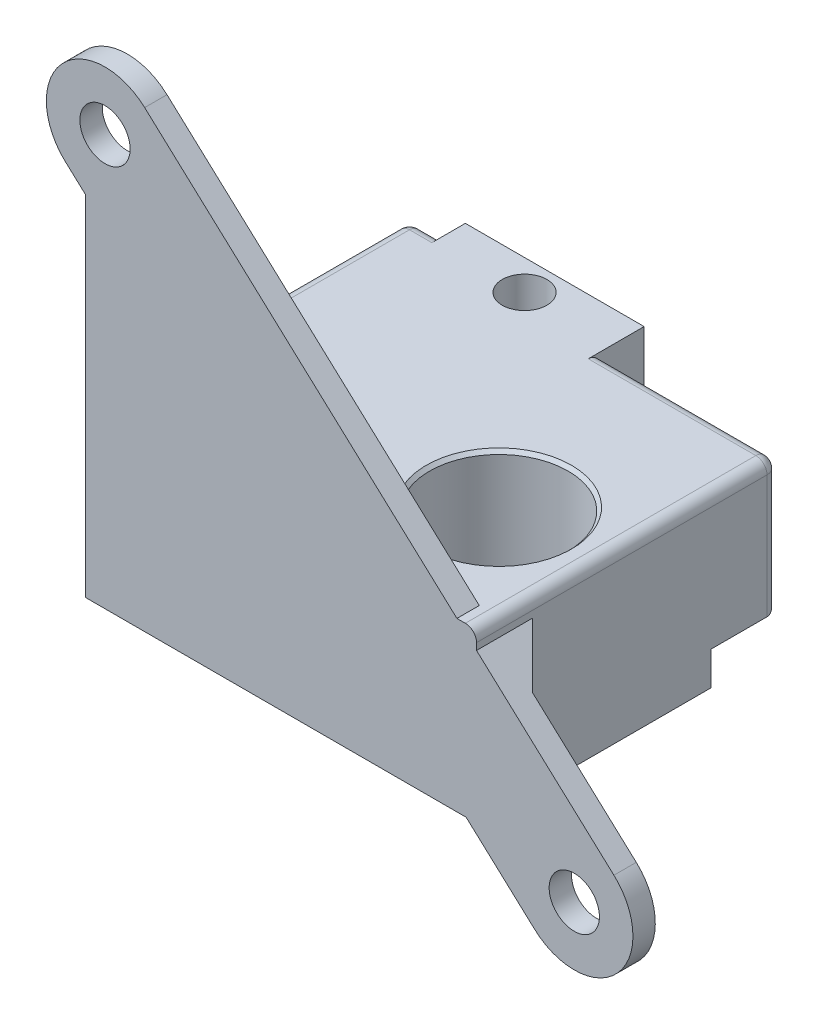
SolidWorks part; units mm, degrees
ref_plane "Front Plane" through (0, 0, 0) normal (0, 0, 1) x (1, 0, 0)
ref_plane "Top Plane" through (0, 0, 0) normal (0, 1, 0) x (1, 0, 0)
ref_plane "Right Plane" through (0, 0, 0) normal (1, 0, 0) x (0, 0, -1)
sketch "Sketch1" plane through (0, 0, 0) normal (0, 0, 1) x (1, 0, 0)
  line L0 (-22.5, 20.5) -> (19.5, -18) construction
  line L5 (-18.9524, 24.3701) -> (23.0476, -14.1299)
  line L6 (-26.0476, 16.6299) -> (15.9524, -21.8701)
  circle A0 centre (-22.5, 20.5) radius 2.25
  circle A1 centre (19.5, -18) radius 2.25
  arc A3 (-18.9524, 24.3701) -> (-26.0476, 16.6299) centre (-22.5, 20.5) ccw
  arc A4 (15.9524, -21.8701) -> (23.0476, -14.1299) centre (19.5, -18) ccw
  point P0 (0, 0)
  point P1 (-1.5, 1.25)
  dimension "D5" = 4.5
  dimension "D6" = 3
  dimension "D1" = 20.5
  dimension "D2" = 18
  dimension "D3" = 22.5
  dimension "D4" = 19.5
extrude "Boss-Extrude1" add sketch "Sketch1" along normal blind 2
sketch "Sketch2" plane through (0, 0, 2) normal (0, 0, -1) x (-1, 0, 0)
  line L0 (-19.5, -23.25) -> (20.25, -23.25) construction
  line L1 (-10.75, -1.25) -> (24.25, -1.25)
  line L2 (-10.75, -1.25) -> (-10.75, -16.25)
  line L3 (-10.75, -16.25) -> (24.25, -16.25)
  line L4 (24.25, -1.25) -> (24.25, -16.25)
  line L5 (20.25, 20.5) -> (20.25, -23.25) construction
  line L7 (20.25, 20.5) -> (22.5, 20.5) construction
  line L8 (-19.5, -23.25) -> (-19.5, -18) construction
  arc A1 (-23.0476, -14.1299) -> (-15.9524, -21.8701) centre (-19.5, -18) ccw construction
  circle A2 centre (22.5, 20.5) radius 2.25 construction
  point P10 (0, 0)
  point P15 (-11.2771, -21.9046)
  dimension "D1" = 4
  dimension "D2" = 15
  dimension "D3" = 35
  dimension "D4" = 7
extrude "Boss-Extrude2" add sketch "Sketch2" along normal blind 31
sketch "Sketch3" plane through (0, 0, -29) normal (0, 0, -1) x (-1, 0, 0)
  line L0 (-10.75, -16.25) -> (24.25, -16.25) construction
  line L6 (22.25, -13.25) -> (22.25, -6.25)
  line L7 (22.25, -6.25) -> (4.25, -6.25)
  line L8 (4.25, -13.25) -> (4.25, -6.25)
  line L9 (-19.5, -18) -> (-19.5, -23.25) construction
  line L10 (-19.5, -23.25) -> (-11.7141, -23.25) construction
  line L11 (22.25, -13.25) -> (24.25, -13.25)
  line L12 (-10.75, -13.25) -> (4.25, -13.25)
  line L13 (-10.75, -13.25) -> (-10.75, -16.25)
  line L14 (-10.75, -16.25) -> (24.25, -16.25)
  line L15 (24.25, -13.25) -> (24.25, -16.25)
  line L16 (24.25, -16.25) -> (24.25, -1.25) construction
  arc A0 (-23.0476, -14.1299) -> (-15.9524, -21.8701) centre (-19.5, -18) ccw construction
  point P2 (-11.292, -21.2737)
  dimension "D1" = 18
  dimension "D2" = 10
  dimension "D4" = 3
  dimension "D5" = 2
extrude "Cut-Extrude1" cut sketch "Sketch3" against normal blind 10
sketch "Sketch4" plane through (0, -1.25, 0) normal (0, 1, 0) x (1, 0, 0)
  line L2 (-22.25, 29) -> (-4.25, 29) construction
  line L3 (-18.9524, 0) -> (-27.75, 0) construction
  circle A0 centre (-13.25, 26.3) radius 2
  point P11 (-13.25, 29)
  dimension "D1" = 4
  dimension "D2" = 26.3
extrude "Cut-Extrude2" cut sketch "Sketch4" against normal through all
sketch "Sketch9" plane through (0, 0, 2) normal (0, 0, -1) x (-1, 0, 0)
  line L0 (24.25, -1.25) -> (24.25, 14.9822)
  line L1 (24.25, 14.9822) -> (6.5422, -1.25)
  line L2 (6.5422, -1.25) -> (24.25, -1.25)
  line L6 (26.0476, 16.6299) -> (6.5422, -1.25) construction
sketch "Sketch14" plane through (0, 0, 2) normal (0, 0, 1) x (1, 0, 0)
  line L0 (10.75, -17.1012) -> (10.75, -16.25)
  line L1 (10.75, -16.25) -> (9.8215, -16.25)
  line L3 (9.8215, -16.25) -> (10.75, -17.1012)
  line L4 (9.8215, -16.25) -> (15.9524, -21.8701) construction
  point P4 (0, 0)
  point P6 (13.0942, -19.25)
  point P8 (10.75, -17.1012)
  point P10 (0, 0)
extrude "Boss-Extrude9" [suppressed] add sketch "Sketch14" against normal blind 2
chamfer "Chamfer1" distance 3 angle 45 1 edges at (10.75, -9.5536, 0)
hole_wizard "Ø12.0mm Clearance Dowel Hole1" positions "Sketch6" profile "Sketch7" hole size "Ø12.0" standard "DIN" end condition through all
sketch "Sketch6" plane through (0, -16.25, 0) normal (0, 1, 0) x (1, 0, 0)
  line L2 (-24.25, 19) -> (-24.25, 0) construction
  line L5 (23.0476, 0) -> (13.75, 0) construction
  line L7 (9.8215, -2) -> (-24.25, -2) construction
  line L8 (-13.25, 26.3) -> (2.25, 8.5) construction
  circle A0 centre (2.25, 8.5) radius 8.5 construction
  point P0 (2.25, 8.5)
  point P51 (0, 0)
  dimension "D1" = 15.5
  dimension "D2" = 10.5
sketch "Sketch7" plane through (2.25, -16.25, -8.5) normal (1, 0, 0) x (0, 0, -1)
  line L0 (0, 0) -> (0, 15)
  line L1 (0, 15) -> (6.5, 15)
  line L2 (6.2, 14.7) -> (6.2, 0.2)
  line L3 (6.2, 0.2) -> (6.4, 0)
  line L5 (6.4, 0) -> (0, 0)
  line L6 (-6.2, 0.2) -> (-6.4, 0) construction
  line L7 (6.5, 15) -> (6.2, 14.7)
  line L8 (-6.5, 15) -> (-6.2, 14.7) construction
  line L11 (0, -6.35) -> (0, 107.95) construction
  dimension "Thru Hole Dia." = 12.4
  dimension "Thru Hole Depth" = 15
  dimension "Near C'Sink Dia." = 12.8
  dimension "Near C'Sink Angle" = 90
  dimension "Far C'Sink Dia." = 13
  dimension "Far C'Sink Angle" = 90
sketch "Sketch10" plane through (0, -16.25, 0) normal (0, -1, 0) x (1, 0, 0)
  circle A0 centre (2.25, -8.5) radius 9.5
  dimension "D1" = 19
sketch "Sketch11" plane through (0, 0, -29) normal (0, 0, -1) x (-1, 0, 0)
  line L0 (4.25, -13.25) -> (-10.75, -13.25) construction
  line L1 (-10.75, -1.25) -> (5.25, -1.25)
  line L2 (-10.75, -1.25) -> (-10.75, -13.25)
  line L3 (-10.75, -13.25) -> (5.25, -13.25)
  line L4 (5.25, -1.25) -> (5.25, -13.25)
  line L5 (4.25, -6.25) -> (4.25, -13.25) construction
  dimension "D1" = 1
extrude "Cut-Extrude4" cut sketch "Sketch11" against normal blind 4
sketch "Sketch13" plane through (0, 0, -29) normal (0, 0, -1) x (-1, 0, 0)
  line L0 (24.25, -13.25) -> (22.25, -13.25) construction
  line L1 (24.25, -1.25) -> (21.25, -1.25)
  line L2 (24.25, -1.25) -> (24.25, -13.25)
  line L3 (24.25, -13.25) -> (21.25, -13.25)
  line L4 (21.25, -1.25) -> (21.25, -13.25)
  line L5 (24.25, -13.25) -> (22.25, -13.25) construction
  line L6 (22.25, -13.25) -> (22.25, -6.25) construction
  dimension "D1" = 1
extrude "Cut-Extrude5" cut sketch "Sketch13" against normal blind 2
extrude "Boss-Extrude7" add sketch "Sketch9" along normal up to surface (2 mm away) up to face at (-20.25, 20.5, 0)
fillet "Fillet1" radius 1 8 edges at (-24.25, -1.25, -13.5) (10.75, -1.25, -11.5) (-22.75, -1.25, -27) (-24.25, -7.25, -27) (-23.25, -13.25, -27) (3.25, -13.25, -25) (2.75, -1.25, -25) (10.75, -7.25, -25)
sketch "Sketch15" plane through (0, -13.25, 0) normal (0, -1, 0) x (1, 0, 0)
  circle A0 centre (-4.25, -19) radius 0.5
  circle A1 centre (-22.25, -19) radius 0.5
  dimension "D1" = 1
extrude "Cut-Extrude6" cut sketch "Sketch15" against normal up to surface (7 mm away) up to face at (-15.25, -6.25, -26.3)
sketch "Sketch16" plane through (-24.25, 0, 0) normal (-1, 0, 0) x (0, 0, 1)
  circle A0 centre (-19, -6.25) radius 0.5
  point P3 (0, 0)
  point P4 (0, 0)
  dimension "D1" = 1
extrude "Cut-Extrude7" cut sketch "Sketch16" against normal up to surface (18 mm away) from surface at -2 up to face at (-4.25, -10.2914, -22.6414) starting at face at (-22.25, -10.2914, -23.8414)
